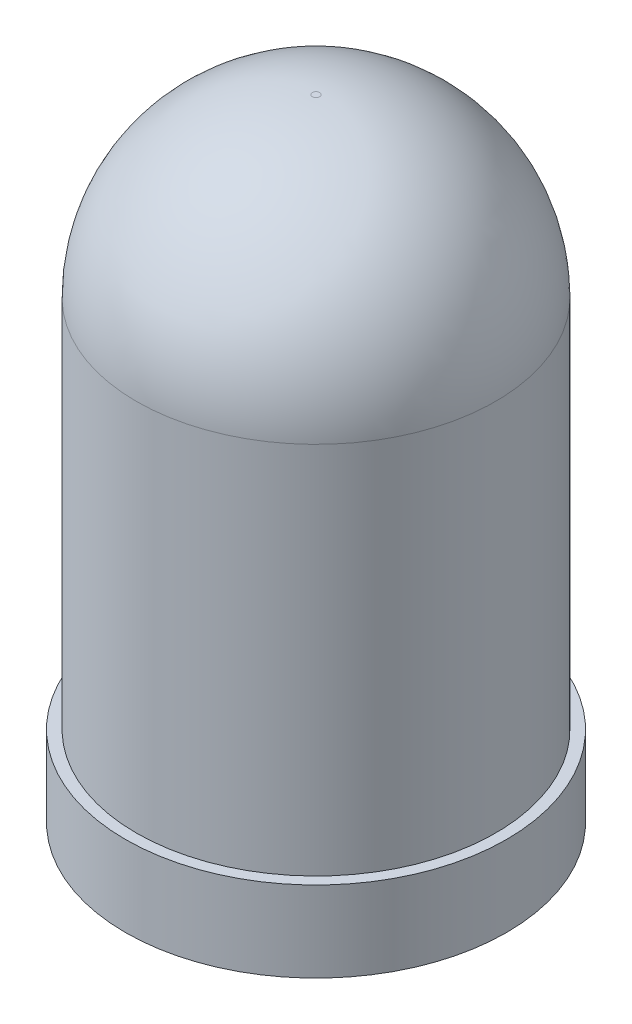
SolidWorks part; units mm, degrees
ref_plane "Alzado" through (0, 0, 0) normal (0, 0, 1) x (1, 0, 0)
ref_plane "Planta" through (0, 0, 0) normal (0, 1, 0) x (1, 0, 0)
ref_plane "Vista lateral" through (0, 0, 0) normal (1, 0, 0) x (0, 0, -1)
sketch "Croquis1" plane through (0, 0, 0) normal (0, 0, 1) x (1, 0, 0)
  line L0 (0, 0) -> (0, 12.0498) construction
  line L1 (0, 0) -> (2.6, 0)
  line L2 (2.6, 0) -> (2.6, 1.1)
  line L3 (2.6, 1.1) -> (2.45, 1.1)
  line L4 (2.45, 1.1) -> (2.45, 6.2)
  line L5 (0.05, 8.6) -> (0, 8.6)
  line L6 (0, 8.6) -> (0, 0)
  arc A0 (2.45, 6.2) -> (0.05, 8.6) centre (0.05, 6.2) ccw
  point P10 (2.45, 8.6)
  dimension "D5" = 2.4
  dimension "D1" = 2.6
  dimension "D2" = 1.1
  dimension "D3" = 8.6
  dimension "D4" = 2.45
revolve "Revolución1" add sketch "Croquis1" angle 360 about L0
